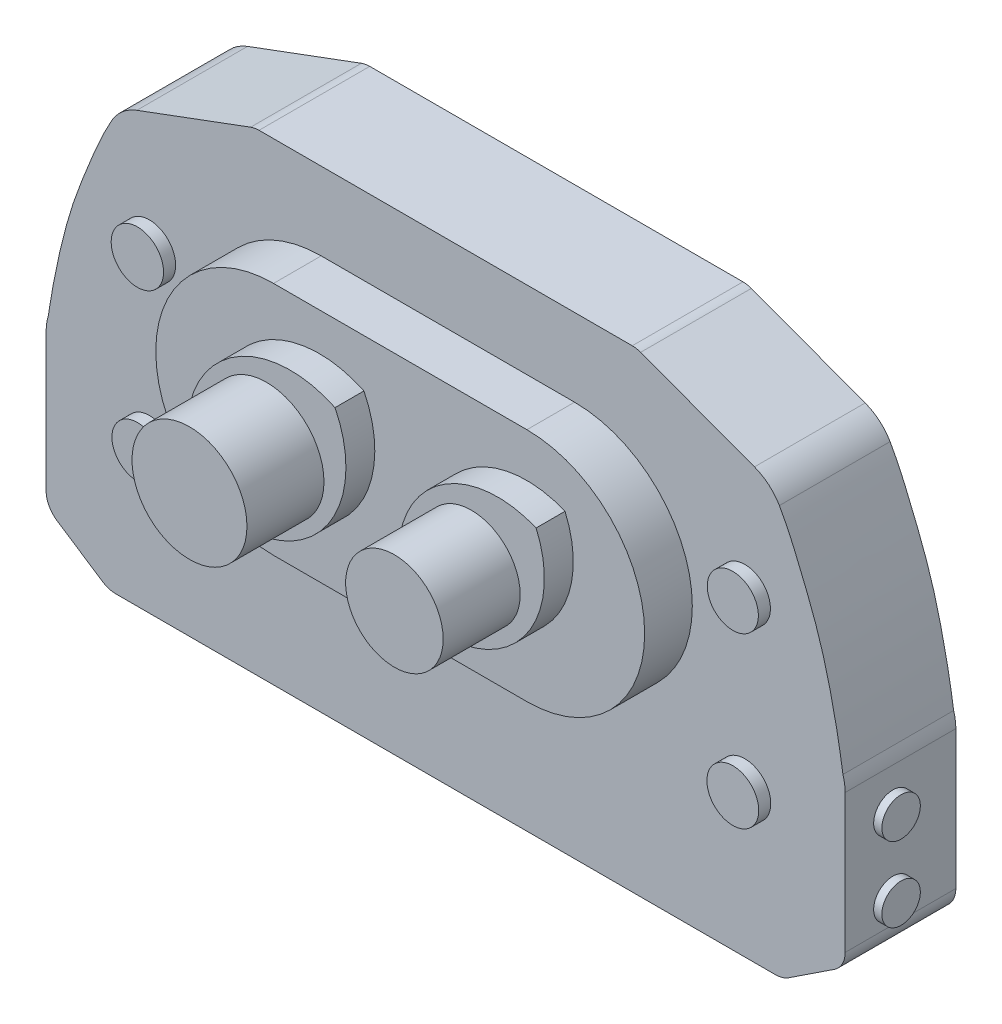
SolidWorks part; units mm, degrees
ref_plane "Front Plane" through (0, 0, 0) normal (0, 0, 1) x (1, 0, 0)
ref_plane "Top Plane" through (0, 0, 0) normal (0, 1, 0) x (1, 0, 0)
ref_plane "Right Plane" through (0, 0, 0) normal (1, 0, 0) x (0, 0, -1)
sketch "Sketch2" plane through (0, 0, 0) normal (0, 0, 1) x (1, 0, 0)
  line L0 (70.5234, -121.2586) -> (80.0018, -115.0085)
  line L1 (82.2493, -110.8343) -> (82.2493, -82.0607)
  line L2 (0, 0) -> (0, 97) construction
  line L3 (122.5391, 337.0673) -> (776.5391, 337.0673) construction
  line L4 (56.1264, 216.4843) -> (710.1264, 216.4843) construction
  line L5 (-39.52, -23.7969) -> (38.0186, -23.7969)
  line L6 (-0.7507, -122.0844) -> (-0.7507, -9.2148) construction
  line L7 (-83.7507, -110.8343) -> (-83.7507, -82.0607)
  line L8 (67.7709, -122.0844) -> (-69.2723, -122.0844)
  line L9 (-72.0248, -121.2586) -> (-81.5032, -115.0085)
  line L10 (-41.261, -24.1098) -> (-64.9089, -32.8935)
  line L11 (39.7596, -24.1098) -> (63.4075, -32.8935)
  line L14 (53.2993, -41.7763) -> (-54.8007, -41.7763) construction
  line L15 (-54.8007, -41.7763) -> (-54.8007, -107.2763) construction
  line L16 (-54.8007, -107.2763) -> (53.2993, -107.2763) construction
  line L17 (53.2993, -107.2763) -> (53.2993, -41.7763) construction
  arc A0 (-70.0862, -37.266) -> (-64.9089, -32.8935) centre (-61.427, -42.2677) cw
  arc A1 (-83.7507, -82.0607) -> (-83.2867, -79.0501) centre (-73.7507, -82.0607) cw
  arc A2 (-81.5032, -115.0085) -> (-83.7507, -110.8343) centre (-78.7507, -110.8343) cw
  arc A3 (-69.2723, -122.0844) -> (-72.0248, -121.2586) centre (-69.2723, -117.0844) cw
  arc A5 (67.7709, -122.0844) -> (70.5234, -121.2586) centre (67.7709, -117.0844) ccw
  arc A6 (80.0018, -115.0085) -> (82.2493, -110.8343) centre (77.2493, -110.8343) ccw
  arc A8 (82.2493, -82.0607) -> (81.7853, -79.0501) centre (72.2493, -82.0607) ccw
  arc A9 (-39.52, -23.7969) -> (-41.261, -24.1098) centre (-39.52, -28.7969) ccw
  arc A10 (68.5848, -37.266) -> (63.4075, -32.8935) centre (59.9256, -42.2677) ccw
  arc A11 (38.0186, -23.7969) -> (39.7596, -24.1098) centre (38.0186, -28.7969) cw
  spline S0 degree 3 poles (-83.2867, -79.0501) (-83.281, -79.0318) (-81.265, -64.2198) (-73.8122, -44.6321) (-71.5907, -39.8705) (-70.0862, -37.266) knots 0.010107 0.010107 0.010107 0.010107 0.430229 0.512694 0.834763 0.834763 0.834763 0.834763
  spline S1 degree 3 poles (81.7853, -79.0501) (81.7796, -79.0318) (79.7636, -64.2198) (72.3108, -44.6321) (70.0893, -39.8705) (68.5848, -37.266) knots 0.010107 0.010107 0.010107 0.010107 0.430229 0.512694 0.834763 0.834763 0.834763 0.834763
  point P5 (0, 0)
  point P13 (-0.7507, -23.7969)
  point P30 (38.9172, -23.7969)
  point P46 (-40.4186, -23.7969)
  point P49 (-0.7507, -41.7763)
  dimension "D1" = 10
  dimension "D2" = 10
  dimension "D3" = 5
  dimension "D4" = 5
  dimension "D5" = 166
  dimension "D6" = 5
extrude "Boss-Extrude1" add sketch "Sketch2" along normal blind 23
sketch "Sketch3" plane through (0, 0, 23) normal (0, 0, 1) x (1, 0, 0)
  line L0 (-0.7507, -23.7969) -> (-0.7507, -122.0844) construction
  line L1 (38.0186, -23.7969) -> (-39.52, -23.7969) construction
  line L2 (-69.2723, -122.0844) -> (67.7709, -122.0844) construction
ref_plane "Plane1" through (-0.7507, 0, 0) normal (-1, 0, 0) x (0, -1, 0)
sketch "Sketch5" plane through (-83.7507, 0, 0) normal (-1, 0, 0) x (0, 0, 1)
  line L0 (-44.9674, 914.2088) -> (400.4847, 914.2088) construction
  line L1 (13.0836, -123.8044) -> (13.0836, -90.5517) construction
  line L2 (-9.5774, -90.5517) -> (13.0836, -90.5517) construction
  line L3 (-9.5774, -106.0696) -> (13.0836, -106.0696) construction
  circle A0 centre (13.0836, -90.5517) radius 4
  circle A1 centre (13.0836, -106.0696) radius 4
extrude "Boss-Extrude3" add sketch "Sketch5" along normal blind 1.7
sketch "Sketch8" plane through (82.2493, 0, 0) normal (1, 0, 0) x (0, 0, -1)
  line L2 (0, -90.5507) -> (-13.08, -90.5507) construction
  line L4 (-13.08, -90.5507) -> (-13.08, -82.0607) construction
  line L6 (-13.08, -90.5507) -> (-13.08, -106.0707) construction
  circle A0 centre (-13.08, -90.5507) radius 4
  circle A1 centre (-13.08, -106.0707) radius 4
extrude "Boss-Extrude4" add sketch "Sketch8" along normal blind 1.7
sketch "Sketch12" plane through (0, 0, 23) normal (0, 0, 1) x (1, 0, 0)
  line L0 (20.3838, 54.9334) -> (416.3838, 54.9334) construction
  line L1 (26.0332, -39.9411) -> (-26.6057, -39.9411)
  line L2 (-26.6057, -39.9411) -> (-26.6057, -88.8696) construction
  line L3 (-26.6057, -88.8696) -> (26.0332, -88.8696)
  line L4 (-0.2862, -39.9411) -> (-0.2862, -88.8696) construction
  arc A0 (-26.6057, -39.9411) -> (-26.6057, -88.8696) centre (-26.6057, -64.4054) ccw
  arc A1 (26.0332, -39.9411) -> (26.0332, -88.8696) centre (26.0332, -64.4054) cw
  circle A2 centre (61.4129, -56.7486) radius 5.3096
  circle A3 centre (61.4129, -91.7846) radius 5.3836
  circle A4 centre (-62.2939, -91.7846) radius 5.291
  circle A5 centre (-62.2939, -56.7486) radius 5.4443
extrude "Boss-Extrude5" add sketch "Sketch12" along normal blind 9.9
sketch "Sketch15" plane through (0, 0, 32.9) normal (0, 0, 1) x (1, 0, 0)
  line L0 (13.4386, 50.6195) -> (409.4386, 50.6195) construction
  line L1 (-7.8316, -49.9018) -> (-36.3069, -78.8976) construction
  line L2 (-0.2862, -39.9411) -> (-0.2862, -88.8696) construction
  line L3 (26.0332, -39.9411) -> (-26.6057, -39.9411) construction
  line L4 (-26.6057, -88.8696) -> (26.0332, -88.8696) construction
  line L5 (-22.0319, -64.3616) -> (20.4621, -64.3616) construction
  line L6 (7.057, -77.9762) -> (33.947, -50.666) construction
  circle A0 centre (-22.0319, -64.3616) radius 11.9456 construction
  arc A1 (-36.3069, -78.8976) -> (-7.8316, -49.9018) centre (-17.0867, -69.2928) cw
  arc A2 (-36.3069, -78.8976) -> (-7.8316, -49.9018) centre (-27.0518, -59.5066) ccw
  circle A3 centre (20.4621, -64.3616) radius 10.1338 construction
  arc A4 (33.947, -50.666) -> (7.057, -77.9762) centre (15.0085, -58.9121) cw
  arc A5 (33.947, -50.666) -> (7.057, -77.9762) centre (25.9955, -69.7301) ccw
extrude "Boss-Extrude6" add sketch "Sketch15" along normal blind 22
sketch "Sketch16" plane through (0, 0, 54.9) normal (0, 0, 1) x (1, 0, 0)
  line L0 (-7.8316, -49.9018) -> (-36.3069, -78.8976) construction
  circle A0 centre (-22.0693, -64.3997) radius 11.94
  arc A1 (-36.3069, -78.8976) -> (-7.8316, -49.9018) centre (-17.0867, -69.2928) cw
  arc A2 (-7.8316, -49.9018) -> (-36.3069, -78.8976) centre (-27.0518, -59.5066) cw
extrude "Cut-Extrude1" cut sketch "Sketch16" against normal blind 16
sketch "Sketch17" plane through (0, 0, 54.9) normal (0, 0, 1) x (1, 0, 0)
  line L0 (33.947, -50.666) -> (7.057, -77.9762) construction
  arc A0 (33.947, -50.666) -> (7.057, -77.9762) centre (25.9955, -69.7301) ccw construction
  arc A1 (7.057, -77.9762) -> (33.947, -50.666) centre (15.0085, -58.9121) ccw construction
  circle A2 centre (20.502, -64.3211) radius 10.13
  arc A3 (7.057, -77.9762) -> (33.947, -50.666) centre (25.9955, -69.7301) cw
  arc A4 (33.947, -50.666) -> (7.057, -77.9762) centre (15.0085, -58.9121) cw
extrude "Cut-Extrude2" cut sketch "Sketch17" against normal blind 16
sketch "Sketch18" plane through (0, 0, 32.9) normal (0, 0, 1) x (1, 0, 0)
  circle A0 centre (61.4129, -56.7486) radius 5.3096
extrude "Cut-Extrude3" cut sketch "Sketch18" against normal blind 7.4
sketch "Sketch19" plane through (0, 0, 32.9) normal (0, 0, 1) x (1, 0, 0)
  circle A0 centre (61.4129, -91.7846) radius 5.3836
extrude "Cut-Extrude4" cut sketch "Sketch19" against normal blind 7.4
sketch "Sketch20" plane through (0, 0, 32.9) normal (0, 0, 1) x (1, 0, 0)
  circle A0 centre (-62.2939, -56.7486) radius 5.4443
extrude "Cut-Extrude5" cut sketch "Sketch20" against normal blind 7.4
sketch "Sketch21" plane through (0, 0, 32.9) normal (0, 0, 1) x (1, 0, 0)
  circle A0 centre (-62.2939, -91.7846) radius 5.291
extrude "Cut-Extrude6" cut sketch "Sketch21" against normal blind 7.4
